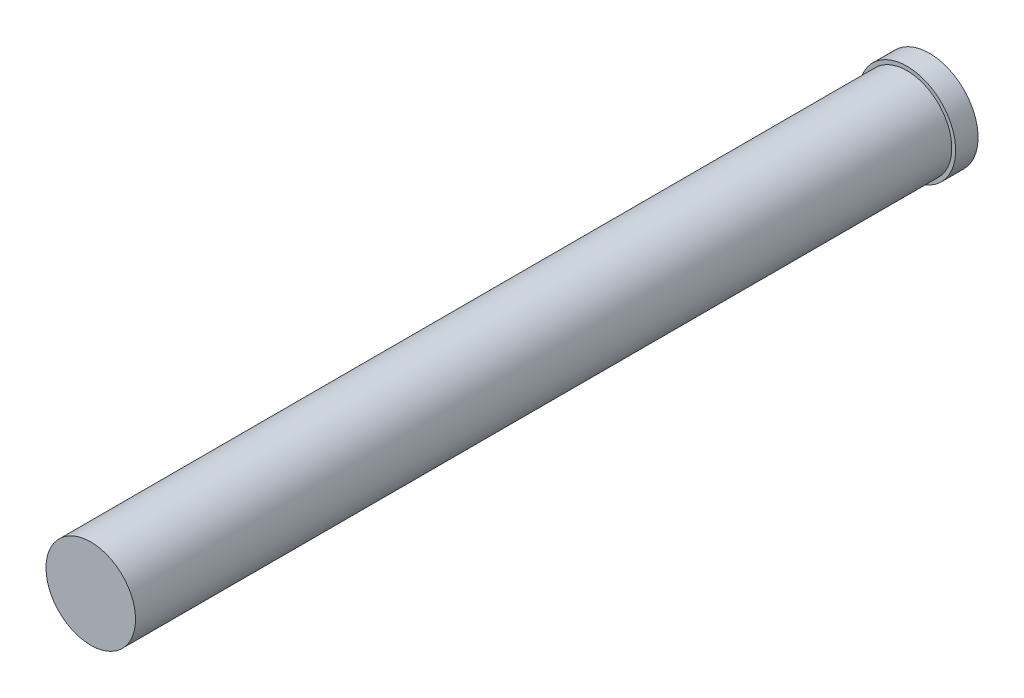
SolidWorks part; units mm, degrees
ref_plane "Front Plane" through (0, 0, 0) normal (0, 0, 1) x (1, 0, 0)
ref_plane "Top Plane" through (0, 0, 0) normal (0, 1, 0) x (1, 0, 0)
ref_plane "Right Plane" through (0, 0, 0) normal (1, 0, 0) x (0, 0, -1)
sketch "Sketch3" plane through (0, 0, 0) normal (0, 0, 1) x (1, 0, 0)
  circle A0 centre (0, 0) radius 19
  dimension "D1" = 38
extrude "Boss-Extrude1" add sketch "Sketch3" along normal blind 356
sketch "Sketch4" plane through (0, 0, 0) normal (0, 0, -1) x (-1, 0, 0)
  circle A0 centre (0, 0) radius 20.6375
  dimension "D1" = 41.275
extrude "Boss-Extrude2" add sketch "Sketch4" against normal blind 9.525 contours A0
sketch "Sketch5" plane through (0, 0, 0) normal (0, 0, -1) x (-1, 0, 0)
  circle A0 centre (0, 0) radius 15
  dimension "D1" = 30
extrude "Cut-Extrude1" cut sketch "Sketch5" against normal blind 300
